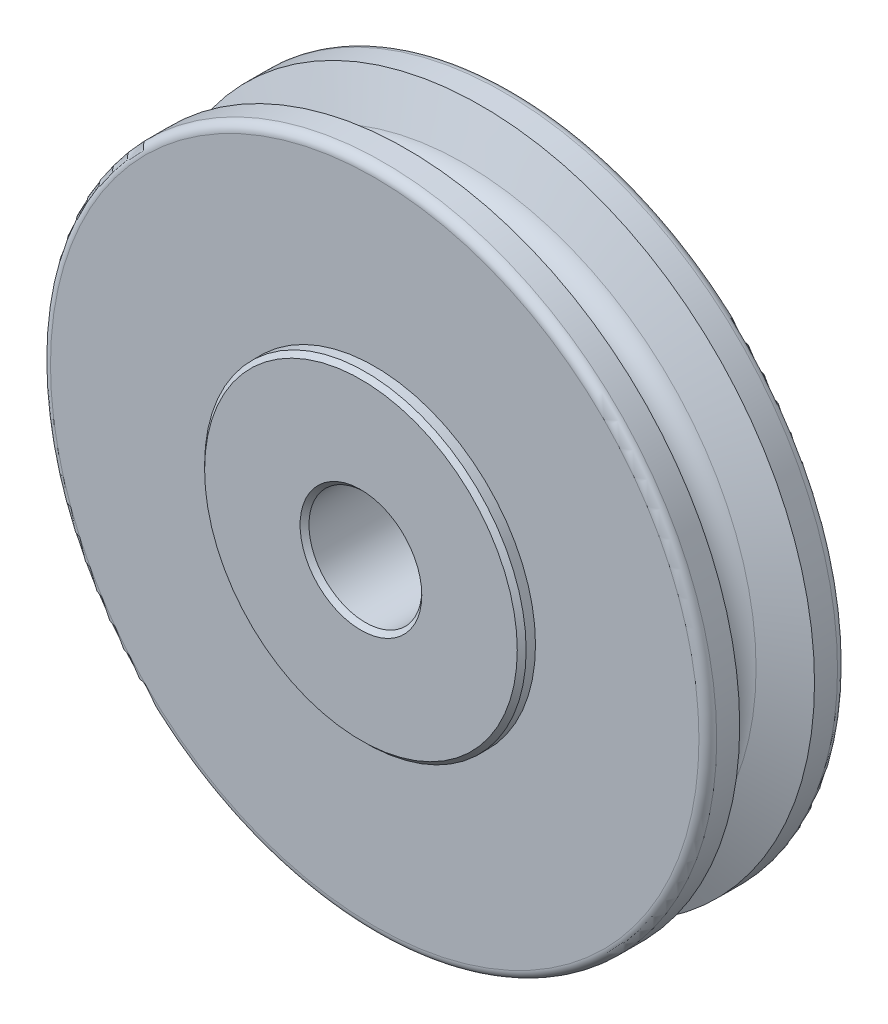
SolidWorks part; units mm, degrees
ref_plane "Front Plane" through (0, 0, 0) normal (0, 0, 1) x (1, 0, 0)
ref_plane "Top Plane" through (0, 0, 0) normal (0, 1, 0) x (1, 0, 0)
ref_plane "Right Plane" through (0, 0, 0) normal (1, 0, 0) x (0, 0, -1)
sketch "Sketch1" plane through (0, 0, 0) normal (1, 0, 0) x (0, 0, -1)
  line L0 (-2.3749, 0) -> (2.3749, 0) construction
  line L1 (0, -7.9375) -> (0, 7.9375) construction
  line L2 (-2.3749, 1.6129) -> (2.3749, 1.6129)
  line L3 (2.3749, 1.6129) -> (2.3749, 4.5974)
  line L4 (2.3749, 4.5974) -> (-2.3749, 4.5974)
  line L5 (-2.3749, 4.5974) -> (-2.3749, 1.6129)
  line L6 (-1.9812, 4.5974) -> (-1.9812, 9.525)
  line L7 (-1.9812, 9.525) -> (-1.0697, 9.525)
  line L8 (-1.0697, 9.525) -> (-0.5888, 8.3346)
  line L9 (1.0697, 9.525) -> (0.5888, 8.3346)
  line L10 (1.9812, 9.525) -> (1.0697, 9.525)
  line L11 (1.9812, 4.5974) -> (1.9812, 9.525)
  line L12 (-1.9812, 9.525) -> (1.9812, 9.525) construction
  arc A0 (-0.5888, 8.3346) -> (0.5888, 8.3346) centre (0, 8.5725) ccw
  circle A1 centre (0, 8.5344) radius 0.5969
  point P4 (0, 0)
  point P8 (0, 0)
  dimension "D1" = 44
  dimension "Pulley Radius (R)" = 0.635
  dimension "For Rope Diameter" = 1.1938
  dimension "Bushing Width (D)" = 4.7498
  dimension "Bushing ID (A)" = 3.2258
  dimension "Pulley Diameter (B)" = 15.875
  dimension "Outside Diameter (C)" = 19.05
  dimension "Sheave Width (E)" = 3.9624
  dimension "Bushing OD" = 9.1948
sketch "Sketch2" plane through (0, 0, 0) normal (1, 0, 0) x (0, 0, -1)
  line L0 (-2.3749, 4.5974) -> (-2.2479, 4.5974) construction
  line L1 (2.3749, 4.5974) -> (-2.3749, 4.5974) construction
  line L2 (-2.3749, 4.5974) -> (-2.3749, 4.4704) construction
  line L3 (-2.3749, 4.5974) -> (-2.3749, 1.6129) construction
  line L4 (-2.3749, 1.6129) -> (-2.3749, 1.7399) construction
  line L5 (-2.3749, 1.6129) -> (-2.2479, 1.6129) construction
  line L6 (-2.3749, 1.6129) -> (2.3749, 1.6129) construction
  line L7 (2.2479, 4.5974) -> (2.3749, 4.5974) construction
  line L8 (2.3749, 4.5974) -> (2.3749, 4.4704) construction
  line L9 (2.3749, 1.6129) -> (2.3749, 4.5974) construction
  line L10 (2.2479, 1.6129) -> (2.3749, 1.6129) construction
  line L11 (2.3749, 1.6129) -> (2.3749, 1.7399) construction
  line L12 (-2.3749, 4.4704) -> (-2.3749, 1.7399)
  line L13 (-2.3749, 1.7399) -> (-2.2479, 1.6129)
  line L14 (-2.2479, 1.6129) -> (2.2479, 1.6129)
  line L15 (2.2479, 1.6129) -> (2.3749, 1.7399)
  line L16 (2.3749, 1.7399) -> (2.3749, 4.4704)
  line L17 (2.3749, 4.4704) -> (2.2479, 4.5974)
  line L18 (2.2479, 4.5974) -> (-2.2479, 4.5974)
  line L19 (-2.2479, 4.5974) -> (-2.3749, 4.4704)
  dimension "D1" = 0.127
revolve "Bushing Revolve" add sketch "Sketch2" angle 360 about L0
sketch "Sketch3" plane through (0, 0, 0) normal (1, 0, 0) x (0, 0, -1)
  line L0 (-1.9812, 4.5974) -> (-1.9812, 9.525) construction
  line L1 (-1.9812, 9.525) -> (-1.0697, 9.525) construction
  line L2 (-1.0697, 9.525) -> (-0.5888, 8.3346) construction
  line L3 (1.0697, 9.525) -> (0.5888, 8.3346) construction
  line L4 (-2.3749, 1.6129) -> (2.3749, 1.6129)
  line L5 (2.3749, 1.6129) -> (2.3749, 4.5974)
  line L6 (2.3749, 4.5974) -> (-2.3749, 4.5974)
  line L7 (-2.3749, 4.5974) -> (-2.3749, 1.6129)
  line L10 (1.9812, 4.5974) -> (-1.9812, 4.5974)
  line L12 (1.9812, 9.525) -> (1.0697, 9.525) construction
  line L13 (1.9812, 4.5974) -> (1.9812, 9.525) construction
  line L14 (-1.9812, 4.5974) -> (-1.9812, 9.271)
  line L15 (-1.7272, 9.525) -> (-1.0697, 9.525)
  line L16 (-1.0697, 9.525) -> (-0.5888, 8.3346)
  line L17 (1.0697, 9.525) -> (0.5888, 8.3346)
  line L18 (1.7272, 9.525) -> (1.0697, 9.525)
  line L19 (1.9812, 4.5974) -> (1.9812, 9.271)
  arc A0 (-0.5888, 8.3346) -> (0.5888, 8.3346) centre (0, 8.5725) ccw construction
  arc A1 (-0.5888, 8.3346) -> (0.5888, 8.3346) centre (0, 8.5725) ccw
  arc A2 (-1.9812, 9.271) -> (-1.7272, 9.525) centre (-1.7272, 9.271) cw
  arc A3 (1.7272, 9.525) -> (1.9812, 9.271) centre (1.7272, 9.271) cw
  dimension "D2" = 0.254
  dimension "D1" = 0
revolve "Sheave Revolve" add sketch "Sketch3" angle 360 about L0
